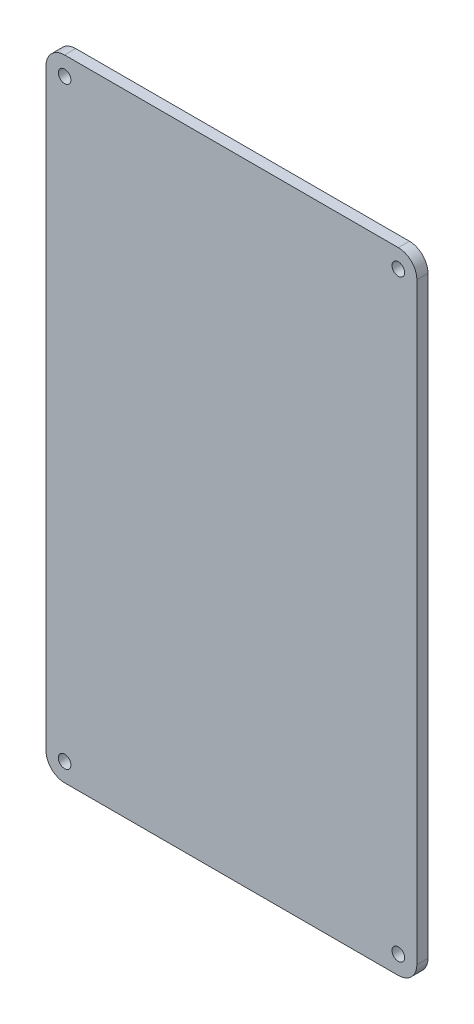
SolidWorks part; units mm, degrees
ref_plane "Front Plane" through (0, 0, 0) normal (0, 0, 1) x (1, 0, 0)
ref_plane "Top Plane" through (0, 0, 0) normal (0, 1, 0) x (1, 0, 0)
ref_plane "Right Plane" through (0, 0, 0) normal (1, 0, 0) x (0, 0, -1)
sketch "Sketch1" plane through (0, 0, 0) normal (0, 0, 1) x (1, 0, 0)
  line L1 (0, 0) -> (100, 0)
  line L2 (0, 0) -> (0, 170)
  line L3 (0, 170) -> (100, 170)
  line L4 (100, 0) -> (100, 170)
  dimension "D1" = 100
  dimension "D2" = 170
extrude "Boss-Extrude1" add sketch "Sketch1" along normal blind 3
hole_wizard "M3 Clearance Hole1" positions "Sketch4" profile "Sketch5" hole size "M3" standard "ANSI Metric"
sketch "Sketch4" plane through (0, 0, 3) normal (0, 0, 1) x (1, 0, 0)
  line L0 (5, 165) -> (5, 85) construction
  line L1 (5, 85) -> (5, 5) construction
  line L2 (5, 5) -> (50, 5) construction
  line L3 (50, 5) -> (95, 5) construction
  line L4 (95, 5) -> (95, 85) construction
  line L5 (95, 85) -> (95, 165) construction
  line L6 (95, 165) -> (50, 165) construction
  line L7 (50, 165) -> (5, 165) construction
  line L10 (0, 170) -> (0, 0) construction
  line L11 (100, 170) -> (0, 170) construction
  line L12 (100, 0) -> (100, 170) construction
  line L13 (0, 0) -> (100, 0) construction
  point P0 (5, 165)
  point P4 (95, 165)
  point P8 (95, 5)
  point P12 (5, 5)
  dimension "D1" = 5
  dimension "D2" = 5
  dimension "D3" = 5
  dimension "D4" = 5
sketch "Sketch5" plane through (5, 165, 3) normal (1, 0, 0) x (0, -1, 0)
  line L0 (0, 0) -> (0, 8.5215)
  line L1 (0, 8.5215) -> (1.7, 7.5)
  line L2 (1.7, 7.5) -> (1.7, 0)
  line L5 (1.7, 0) -> (0, 0)
  line L10 (0, 8.5215) -> (-1.7, 7.5) construction
  line L11 (0, -6.35) -> (0, 107.95) construction
  dimension "Hole Dia." = 3.4
  dimension "Hole Depth" = 7.5
  dimension "Drill Angle" = 118
fillet "Fillet1" radius 5 4 edges at (100, 170, 1.5) (100, 0, 1.5) (0, 0, 1.5) (0, 170, 1.5)
